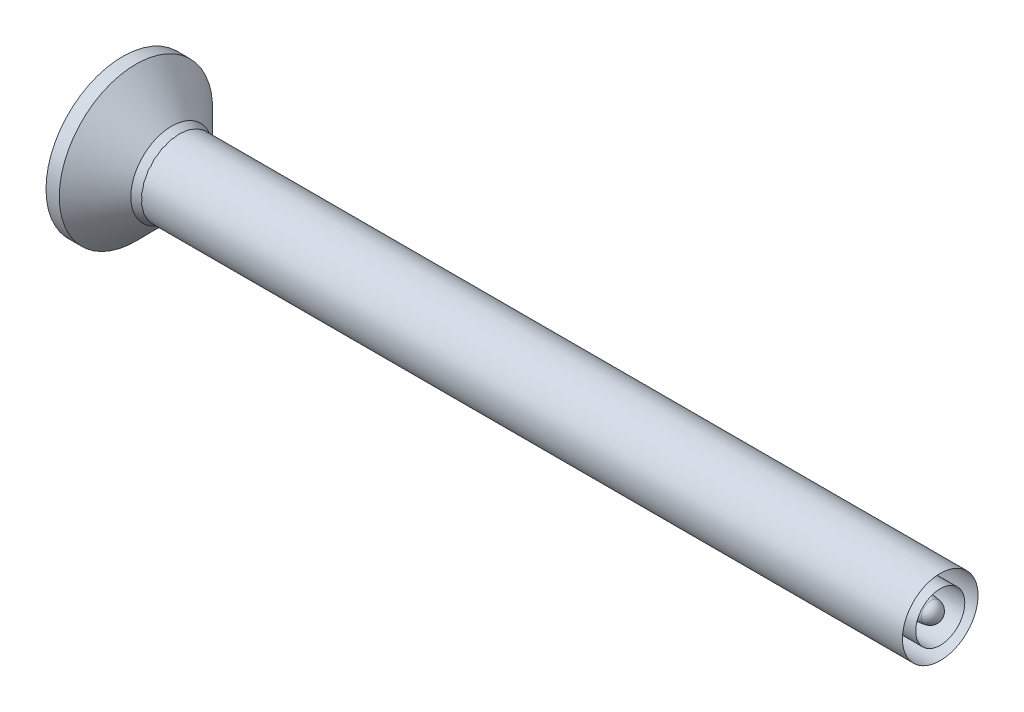
SolidWorks part; units mm, degrees
ref_plane "Front Plane" through (0, 0, 0) normal (0, 0, 1) x (1, 0, 0)
ref_plane "Top Plane" through (0, 0, 0) normal (0, 1, 0) x (1, 0, 0)
ref_plane "Right Plane" through (0, 0, 0) normal (1, 0, 0) x (0, 0, -1)
sketch "Sketch1" plane through (0, 0, 0) normal (0, 0, 1) x (1, 0, 0)
  line L0 (0, -4.7625) -> (0, 0)
  line L1 (0, 4.7625) -> (0.8255, 4.7625) construction
  line L2 (0.8255, 4.7625) -> (3.048, 2.54) construction
  line L3 (3.048, 2.54) -> (5.08, 1.7463) construction
  line L4 (5.08, 1.7463) -> (5.08, -1.7463) construction
  line L5 (5.08, -1.7463) -> (3.048, -2.54)
  line L6 (3.048, -2.54) -> (0.8255, -4.7625)
  line L7 (0.8255, -4.7625) -> (0, -4.7625)
  line L8 (0.8255, 4.7625) -> (0.8255, -4.7625) construction
  line L9 (3.048, 2.54) -> (3.048, -2.54) construction
  line L10 (0, 0) -> (50.165, 0) construction
  line L11 (5.08, 1.7463) -> (41.7658, 1.7463) construction
  line L12 (5.08, -1.7463) -> (27.94, -1.7463)
  line L13 (43.454, -1.524) -> (50.2479, -0.6296)
  line L14 (50.2479, 0.6296) -> (41.7658, 1.7463) construction
  line L15 (41.7658, 1.7463) -> (41.7658, -1.7463) construction
  line L16 (50.2479, -0.6296) -> (55.0299, 0) construction
  line L17 (55.0299, 0) -> (50.2479, 0.6296) construction
  line L18 (0, 0) -> (50.8, 0)
  line L19 (0, 0) -> (0, 4.7625) construction
  line L20 (27.94, -1.7463) -> (29.6282, -1.524)
  line L22 (29.6282, -1.524) -> (43.454, -1.524)
  line L23 (27.94, -1.7463) -> (41.7658, -1.7463) construction
  line L24 (41.7658, -1.7463) -> (43.454, -1.524) construction
  line L25 (29.6282, -1.524) -> (29.6282, 1.524) construction
  arc A0 (50.8, 0) -> (50.2479, -0.6296) centre (50.165, 0) cw
  arc A1 (50.2479, 0.6296) -> (50.8, 0) centre (50.165, 0) cw construction
  point P3 (29.6282, 0)
  point P14 (5.08, 0)
  dimension "D10" = 0.635
  dimension "D1" = 9.525
  dimension "D2" = 3.048
  dimension "D3" = 45
  dimension "D4" = 45
  dimension "D5" = 5.08
  dimension "D6" = 3.4925
  dimension "D7" = 5.08
  dimension "D8" = 50.8
  dimension "D9" = 15
  dimension "D11" = 7.5
  dimension "D12" = 3.048
  dimension "D13" = 22.86
revolve "Revolve1" add sketch "Sketch1" angle 360 about L18
sketch "Sketch2" plane through (0, 0, 0) normal (1, 0, 0) x (0, 0, -1)
  circle A1 centre (0, 0) radius 1.524
  circle A2 centre (0, 0) radius 1.524 construction
surface "Max Pre-Drill Diameter" sketch "Sketch2"
sketch "Sketch3" plane through (0, 0, 0) normal (-1, 0, 0) x (0, 0, 1)
  circle A0 centre (0, 0) radius 2.3495
  dimension "D1" = 4.699
surface "Thread Diameter" sketch "Sketch3"
